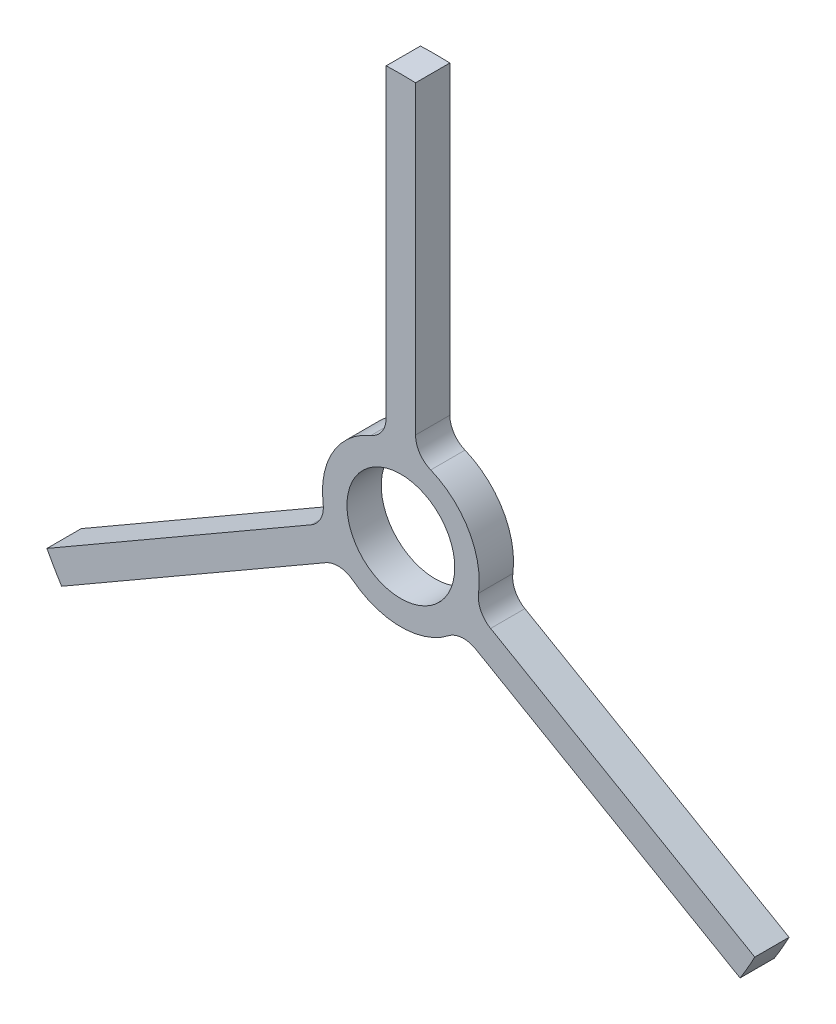
SolidWorks part; units mm, degrees
ref_plane "Front Plane" through (0, 0, 0) normal (0, 0, 1) x (1, 0, 0)
ref_plane "Top Plane" through (0, 0, 0) normal (0, 1, 0) x (1, 0, 0)
ref_plane "Right Plane" through (0, 0, 0) normal (1, 0, 0) x (0, 0, -1)
sketch "Sketch1" plane through (0, 0, 0) normal (0, 0, 1) x (1, 0, 0)
  line L2 (-3, 15.7162) -> (-3, 81.6691)
  line L12 (-15.1107, -5.26) -> (-72.2275, -38.2365)
  line L13 (-12.1107, -10.4562) -> (-69.2275, -43.4326)
  line L14 (12.1107, -10.4562) -> (69.2275, -43.4326)
  line L15 (15.1107, -5.26) -> (72.2275, -38.2365)
  line L16 (3, 15.7162) -> (3, 81.6691)
  circle A0 centre (0, 0) radius 11
  arc A1 (-3, 15.7162) -> (-15.1107, -5.26) centre (0, 0) ccw
  arc A2 (3, 81.6691) -> (-3, 81.6691) centre (0, 0) ccw
  circle A3 centre (0, 0) radius 16 construction
  arc A4 (15.1107, -5.26) -> (3, 15.7162) centre (0, 0) ccw
  arc A5 (-12.1107, -10.4562) -> (12.1107, -10.4562) centre (0, 0) ccw
  arc A6 (69.2275, -43.4326) -> (72.2275, -38.2365) centre (0, 0) ccw
  arc A7 (-72.2275, -38.2365) -> (-69.2275, -43.4326) centre (0, 0) ccw
  point P24 (0, 0)
  dimension "D1" = 22
  dimension "D3" = 163.4483
  dimension "D2" = 5
extrude "Boss-Extrude1" add sketch "Sketch1" along normal blind 7
fillet "Fillet1" radius 5 6 edges at (-3, 15.7162, 3.5) (-15.1107, -5.26, 3.5) (-12.1107, -10.4562, 3.5) (12.1107, -10.4562, 3.5) (15.1107, -5.26, 3.5) (3, 15.7162, 3.5)
equation "\"D3@Sketch1\"=4740/29"
